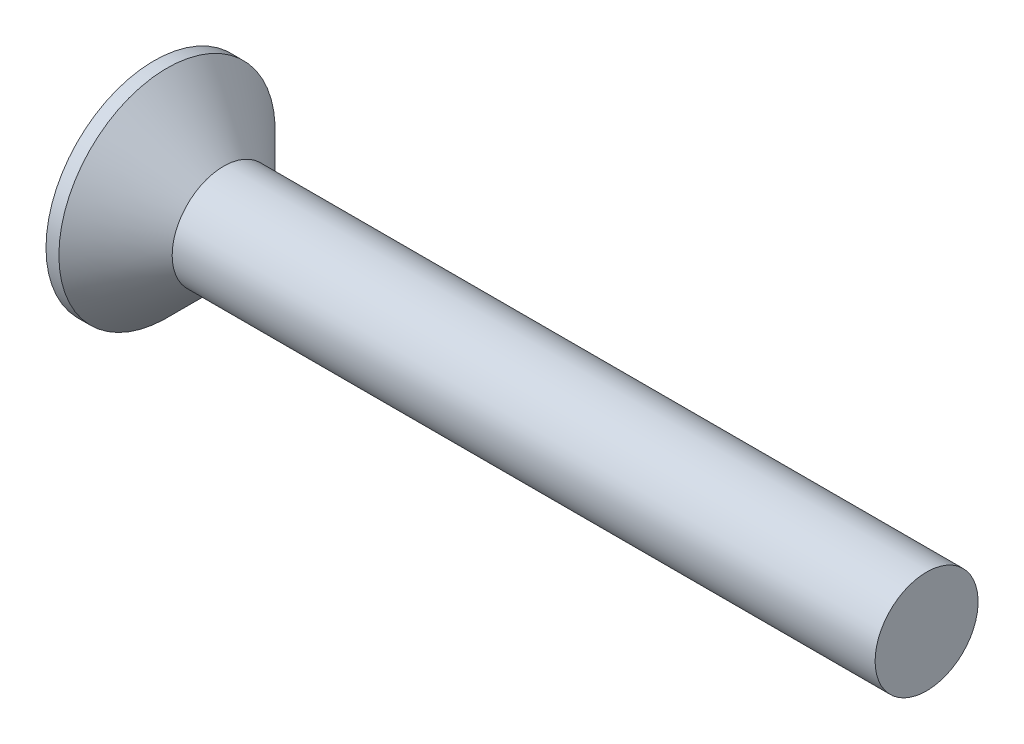
SolidWorks part; units mm, degrees
ref_plane "Plan de face" through (0, 0, 0) normal (0, 0, 1) x (1, 0, 0)
ref_plane "Plan de dessus" through (0, 0, 0) normal (0, 1, 0) x (1, 0, 0)
ref_plane "Plan de droite" through (0, 0, 0) normal (1, 0, 0) x (0, 0, -1)
sketch "Esquisse1" plane through (0, 0, 0) normal (0, 0, 1) x (1, 0, 0)
  line L0 (0, 0) -> (30, 0)
  line L1 (30, 0) -> (30, 2)
  line L2 (30, 2) -> (2.7, 2)
  line L4 (0, 4.2) -> (0, 0)
  line L5 (0, 4.2) -> (0.5, 4.2)
  line L6 (0.5, 4.2) -> (2.7, 2)
  dimension "D1" = 30
  dimension "D2" = 2
  dimension "D3" = 4.2
  dimension "D4" = 2.7
  dimension "D5" = 45
revolve "Révolution1" add sketch "Esquisse1" angle 360 about L0
equation "\"D3@Esquisse1\"=8.4/2"
